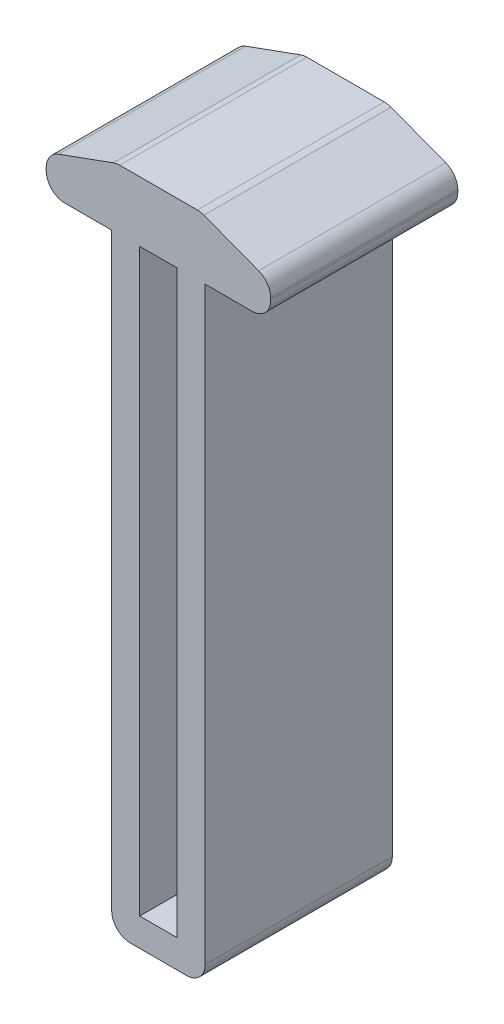
SolidWorks part; units mm, degrees
ref_plane "Plan de face" through (0, 0, 0) normal (0, 0, 1) x (1, 0, 0)
ref_plane "Plan de dessus" through (0, 0, 0) normal (0, 1, 0) x (1, 0, 0)
ref_plane "Plan de droite" through (0, 0, 0) normal (1, 0, 0) x (0, 0, -1)
sketch "Esquisse1" plane through (0, 0, 0) normal (0, 0, 1) x (1, 0, 0)
  line L1 (10.5514, 0) -> (10.5514, 1.8058)
  line L2 (10.5514, 1.8058) -> (6.8111, 3.2235)
  line L3 (6.8111, 3.2235) -> (2.3111, 3.2235)
  line L4 (2.3111, 3.2235) -> (-1.4486, 1.858)
  line L5 (-1.4486, 1.858) -> (-1.4486, 0)
  line L6 (3.5514, 0) -> (3.5514, -31)
  line L7 (3.5514, -31) -> (5.5514, -31)
  line L8 (5.5514, -31) -> (5.5514, 0)
  line L9 (-1.4486, 0) -> (2.0514, 0)
  line L10 (7.0514, 0) -> (7.0514, -32.5)
  line L11 (7.0514, -32.5) -> (2.0514, -32.5)
  line L12 (2.0514, -32.5) -> (2.0514, 0)
  line L13 (3.5514, 0) -> (5.5514, 0)
  line L14 (7.0514, 0) -> (10.5514, 0)
  point P2 (10.0514, 1.858)
  dimension "D1" = 1.5
  dimension "D2" = 4.5
  dimension "D3" = 4
  dimension "D4" = 4
  dimension "D5" = 2
  dimension "D6" = 3.5
  dimension "D7" = 1.5
  dimension "D8" = 3.5
  dimension "D9" = 1.5
  dimension "D10" = 31
extrude "Boss.-Extru.1" add sketch "Esquisse1" along normal blind 10
fillet "Congé1" radius 1 8 edges at (2.0514, -32.5, 5) (7.0514, -32.5, 5) (-1.4486, 0, 5) (10.5514, 0, 5) (10.5514, 1.8058, 5) (6.8111, 3.2235, 5) (2.3111, 3.2235, 5) (-1.4486, 1.858, 5)
